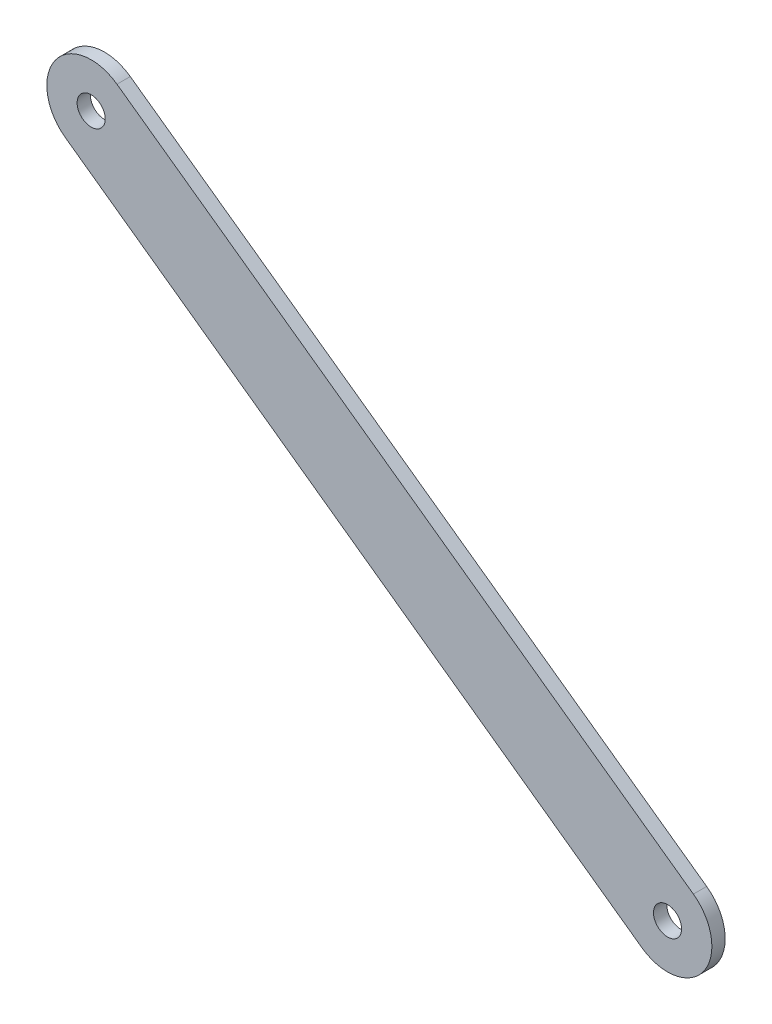
SolidWorks part; units mm, degrees
ref_plane "Front Plane" through (0, 0, 0) normal (0, 0, 1) x (1, 0, 0)
ref_plane "Top Plane" through (0, 0, 0) normal (0, 1, 0) x (1, 0, 0)
ref_plane "Right Plane" through (0, 0, 0) normal (1, 0, 0) x (0, 0, -1)
sketch "Sketch1" plane through (0, 0, 0) normal (0, 0, 1) x (1, 0, 0)
  line L0 (213.4419, -24.9376) -> (83.4011, 68.2792) construction
  line L1 (83.4011, 68.2792) -> (89.2271, 76.4068) construction
  line L2 (89.2271, 76.4068) -> (219.2679, -16.8101)
  line L3 (77.575, 60.1516) -> (207.6158, -33.0652)
  circle A0 centre (83.4011, 68.2792) radius 3.1677
  arc A1 (89.2271, 76.4068) -> (77.575, 60.1516) centre (83.4011, 68.2792) ccw
  circle A2 centre (213.4419, -24.9376) radius 3.1677
  arc A3 (207.6158, -33.0652) -> (219.2679, -16.8101) centre (213.4419, -24.9376) ccw
  dimension "D1" = 10
  dimension "D2" = 10
  dimension "D3" = 160
extrude "Boss-Extrude1" add sketch "Sketch1" along normal blind 3 contours L3 A3 L2 A1 A0 A2
sketch "Sketch2" [suppressed] plane through (0, 0, 3) normal (0, 0, 1) x (1, 0, 0)
  line L0 (89.2271, 76.4068) -> (40.4618, 111.3631)
  line L1 (28.8097, 95.108) -> (77.575, 60.1516)
  line L2 (89.2271, 76.4068) -> (243.6506, -34.2883) construction
  line L4 (77.575, 60.1516) -> (231.9985, -50.5434)
  line L5 (243.6506, -34.2883) -> (89.2271, 76.4068)
  arc A4 (40.4618, 111.3631) -> (28.8097, 95.108) centre (34.6357, 103.2355) ccw
  arc A6 (231.9985, -50.5434) -> (243.6506, -34.2883) centre (237.8245, -42.4158) ccw
  arc A7 (89.2271, 76.4068) -> (77.575, 60.1516) centre (83.4011, 68.2792) ccw
  arc A9 (89.2271, 76.4068) -> (77.575, 60.1516) centre (83.4011, 68.2792) ccw
  arc M12 (89.2271, 76.4068) -> (77.575, 60.1516) centre (83.4011, 68.2792) ccw
  dimension "D1" = 60
  dimension "D2" = 0
extrude "Boss-Extrude2" [suppressed] add sketch "Sketch2" against normal blind 3 contours L0 A4 L1 M12
sketch "Sketch3" [suppressed] plane through (0, 0, 3) normal (0, 0, 1) x (1, 0, 0)
  circle A0 centre (34.6357, 103.2355) radius 3
  circle A8 centre (46.8271, 94.4964) radius 3
  circle A9 centre (59.0184, 85.7574) radius 3
  circle A10 centre (71.2097, 77.0183) radius 3
  circle A11 centre (83.4011, 68.2792) radius 3
  circle A12 centre (95.5924, 59.5401) radius 3
  circle A13 centre (107.7837, 50.801) radius 3
  dimension "D1" = 7
sketch "Sketch4" [suppressed] plane through (0, 0, 3) normal (0, 0, 1) x (1, 0, 0)
  circle A0 centre (83.4011, 68.2792) radius 3.1677
extrude "Boss-Extrude4" [suppressed] add sketch "Sketch4" against normal blind 3
extrude "Cut-Extrude1" [suppressed] cut sketch "Sketch3" against normal blind 3
